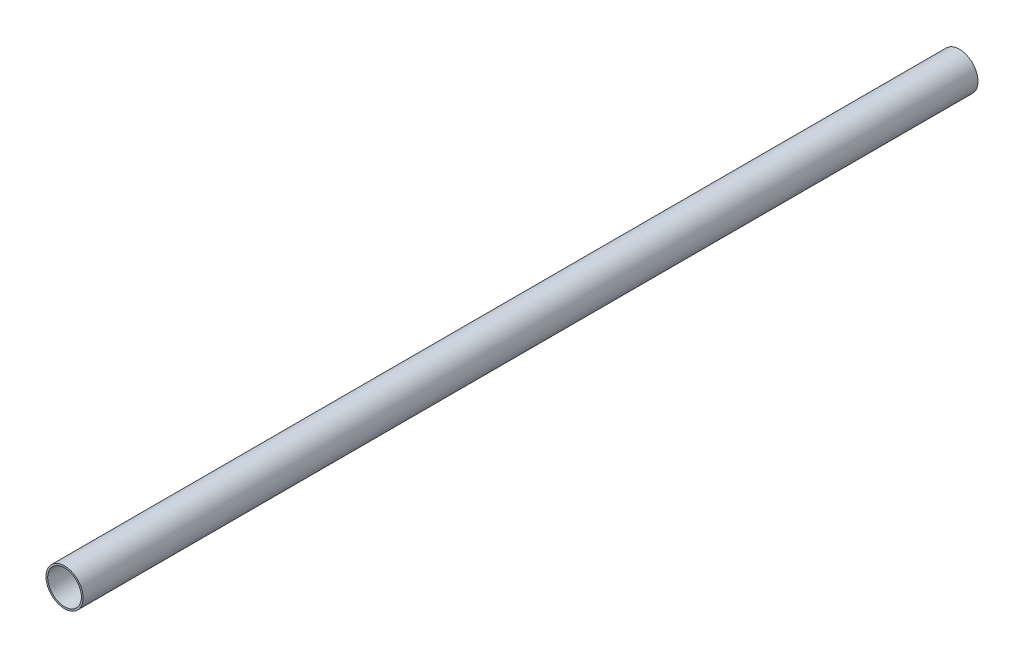
SolidWorks part; units mm, degrees
material "Acier galvanisé"
ref_plane "Plan de face" through (0, 0, 0) normal (0, 0, 1) x (1, 0, 0)
ref_plane "Plan de dessus" through (0, 0, 0) normal (0, 1, 0) x (1, 0, 0)
ref_plane "Plan de droite" through (0, 0, 0) normal (1, 0, 0) x (0, 0, -1)
sketch "Esquisse1" plane through (0, 0, 0) normal (0, 0, 1) x (1, 0, 0)
  circle A0 centre (0, 0) radius 17.4625
  circle A1 centre (0, 0) radius 19.2405
  dimension "D1" = 34.925
  dimension "D2" = 38.481
extrude "Boss.-Extru.1" add sketch "Esquisse1" along normal blind 965.2
sketch "Esquisse2" plane through (0, 0, 0) normal (0, 1, 0) x (1, 0, 0)
  line L0 (19.2405, -965.2) -> (19.2405, 0) construction
  line L1 (-19.2405, 0) -> (19.2405, 0)
  line L2 (-19.2405, 0) -> (-19.2405, -38.1)
  line L3 (-19.2405, -38.1) -> (19.2405, -38.1)
  line L4 (19.2405, 0) -> (19.2405, -38.1)
  dimension "D1" = 38.1
extrude "Enlèv. mat.-Extru.1" cut sketch "Esquisse2" against normal through all and the other way through all
